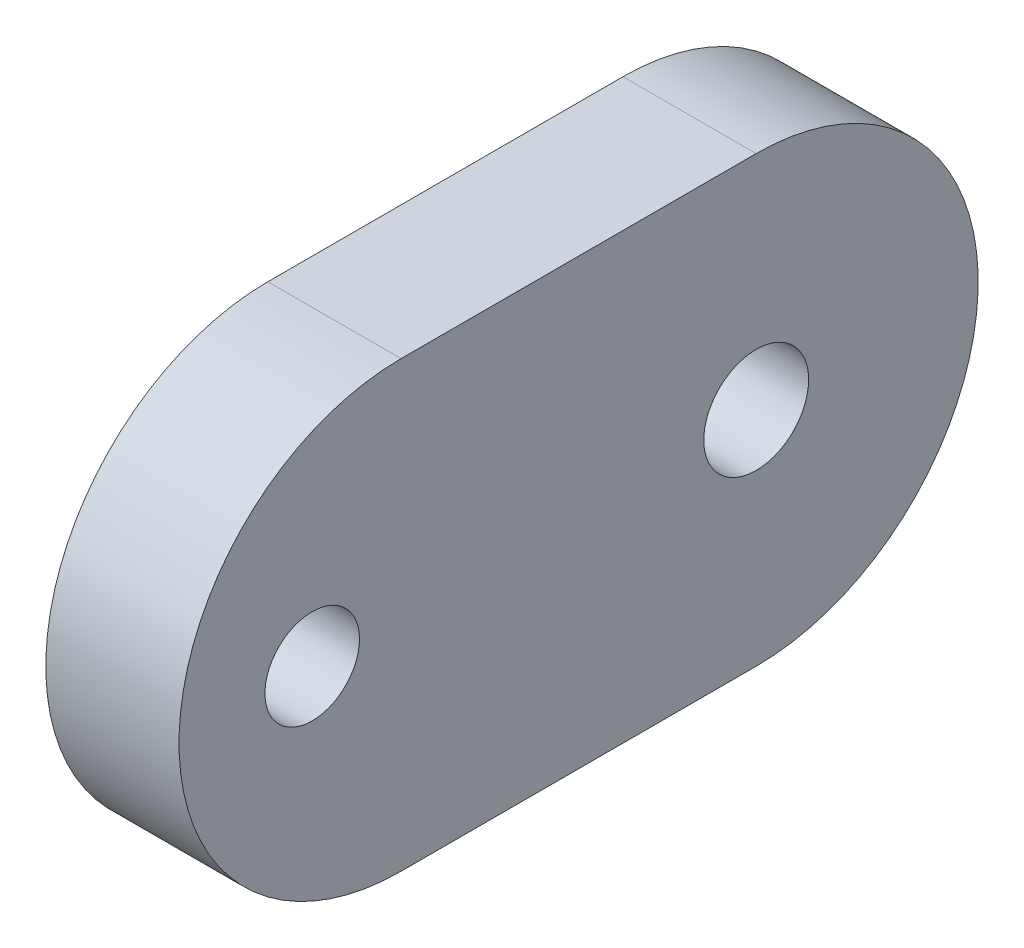
SolidWorks part; units mm, degrees
ref_plane "Front Plane" through (0, 0, 0) normal (0, 0, 1) x (1, 0, 0)
ref_plane "Top Plane" through (0, 0, 0) normal (0, 1, 0) x (1, 0, 0)
ref_plane "Right Plane" through (0, 0, 0) normal (1, 0, 0) x (0, 0, -1)
sketch "Sketch1" plane through (0, 0, 0) normal (1, 0, 0) x (0, 0, -1)
  line L1 (0, 0) -> (10.16, 0)
  line L3 (0, 12.7) -> (10.16, 12.7)
  arc A0 (0, 12.7) -> (0, 0) centre (0, 6.35) ccw
  arc A1 (10.16, 12.7) -> (10.16, 0) centre (10.16, 6.35) cw
  dimension "D1" = 12.7
  dimension "D2" = 10.16
extrude "Boss-Extrude1" add sketch "Sketch1" along normal blind 3.81
hole_wizard "#6-32 Tapped Hole1" positions "Sketch3" profile "Sketch2" tap size "#6-32" standard "ANSI Inch" end condition through all
sketch "Sketch3" plane through (3.81, 0, 0) normal (1, 0, 0) x (0, 0, -1)
  arc A0 (0, 12.7) -> (0, 0) centre (0, 6.35) ccw construction
  point P0 (-2.54, 6.35)
  point P8 (-6.35, 6.35)
  dimension "D1" = 3.81
sketch "Sketch2" plane through (3.81, 6.35, 2.54) normal (0, 1, 0) x (0, 0, -1)
  line L0 (0, 0) -> (0, 3.81)
  line L1 (0, 3.81) -> (1.3525, 3.81)
  line L2 (1.3525, 3.81) -> (1.3525, 0)
  line L5 (1.3525, 0) -> (0, 0)
  line L11 (0, -6.35) -> (0, 107.95) construction
  dimension "Thread Major Dia." = 2.7051
  dimension "Thru Tap Drill Depth" = 3.81
hole_wizard "Ø3.0mm Dowel Hole1" positions "Sketch5" profile "Sketch4" hole size "Ø3.0" standard "ISO" end condition through all
sketch "Sketch5" plane through (3.81, 0, 0) normal (1, 0, 0) x (0, 0, -1)
  point P0 (10.16, 6.35)
sketch "Sketch4" plane through (3.81, 6.35, -10.16) normal (0, 1, 0) x (0, 0, -1)
  line L0 (0, 0) -> (0, 3.81)
  line L1 (0, 3.81) -> (1.5, 3.81)
  line L2 (1.5, 3.81) -> (1.5, 0)
  line L5 (1.5, 0) -> (0, 0)
  line L11 (0, -6.35) -> (0, 107.95) construction
  dimension "Thru Hole Dia." = 3
  dimension "Thru Hole Depth" = 3.81
